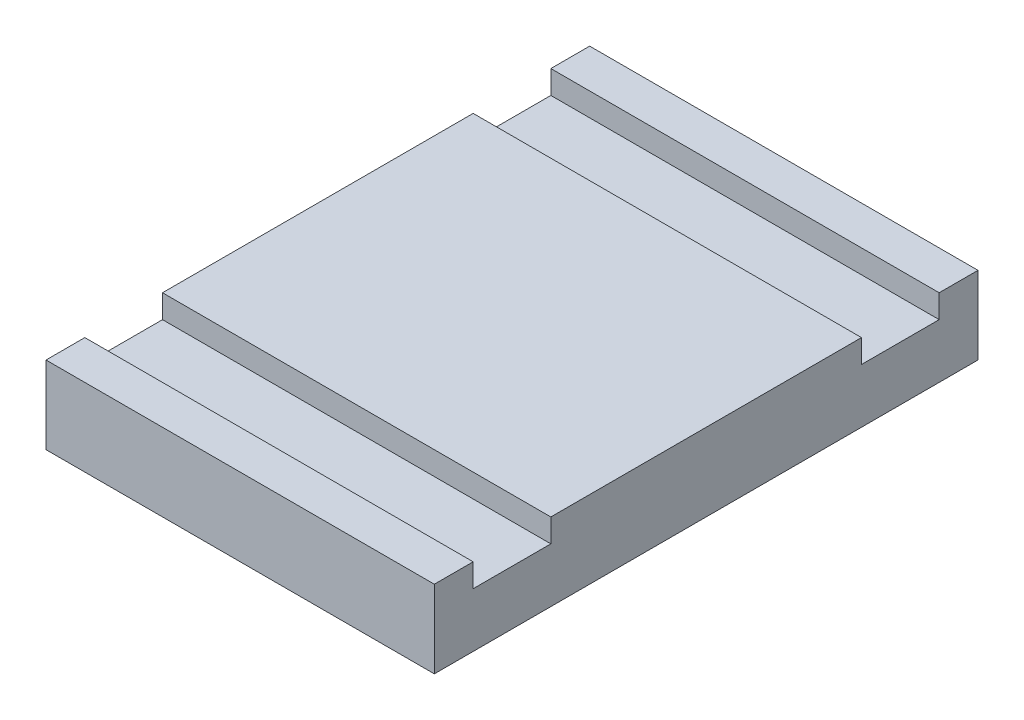
SolidWorks part; units mm, degrees
other "Published References"
other "Ground Plane"
other "Connector1"
other "Connector2"
material "Beech"
ref_plane "Front Plane" through (0, 0, 0) normal (0, 0, 1) x (1, 0, 0)
ref_plane "Top Plane" through (0, 0, 0) normal (0, 1, 0) x (1, 0, 0)
ref_plane "Right Plane" through (0, 0, 0) normal (1, 0, 0) x (0, 0, -1)
sketch "Sketch1" plane through (0, 0, 0) normal (0, 1, 0) x (1, 0, 0)
  line L0 (0, -35) -> (50, -35)
  line L1 (50, -35) -> (50, 35)
  line L2 (50, 35) -> (0, 35)
  line L3 (0, 35) -> (0, -35)
  point P6 (0, 0)
  dimension "D1" = 70
  dimension "D2" = 50
extrude "Boss-Extrude1" add sketch "Sketch1" along normal blind 10
sketch "Sketch3" plane through (0, 0, 0) normal (-1, 0, 0) x (0, 0, 1)
  line L0 (-35, 10) -> (35, 10) construction
  line L1 (-30, 10) -> (-20, 10)
  line L2 (-30, 10) -> (-30, 7)
  line L3 (-30, 7) -> (-20, 7)
  line L4 (-20, 10) -> (-20, 7)
  line L5 (0, 0) -> (0, 10) construction
  line L6 (20, 10) -> (20, 7)
  line L7 (30, 7) -> (20, 7)
  line L8 (30, 10) -> (30, 7)
  line L9 (30, 10) -> (20, 10)
  line L10 (-35, 0) -> (35, 0) construction
  point P14 (-25, 7)
  point P15 (25, 7)
  dimension "D1" = 50
  dimension "D2" = 10
  dimension "D3" = 3
extrude "Cut-Extrude1" cut sketch "Sketch3" against normal through all
sketch "Sketch4" plane through (0, 10, 0) normal (0, 1, 0) x (1, 0, 0)
  line L0 (0, 0) -> (50, 0)
  line L1 (0, 20) -> (0, -20) construction
  line L2 (50, -20) -> (50, 20) construction
